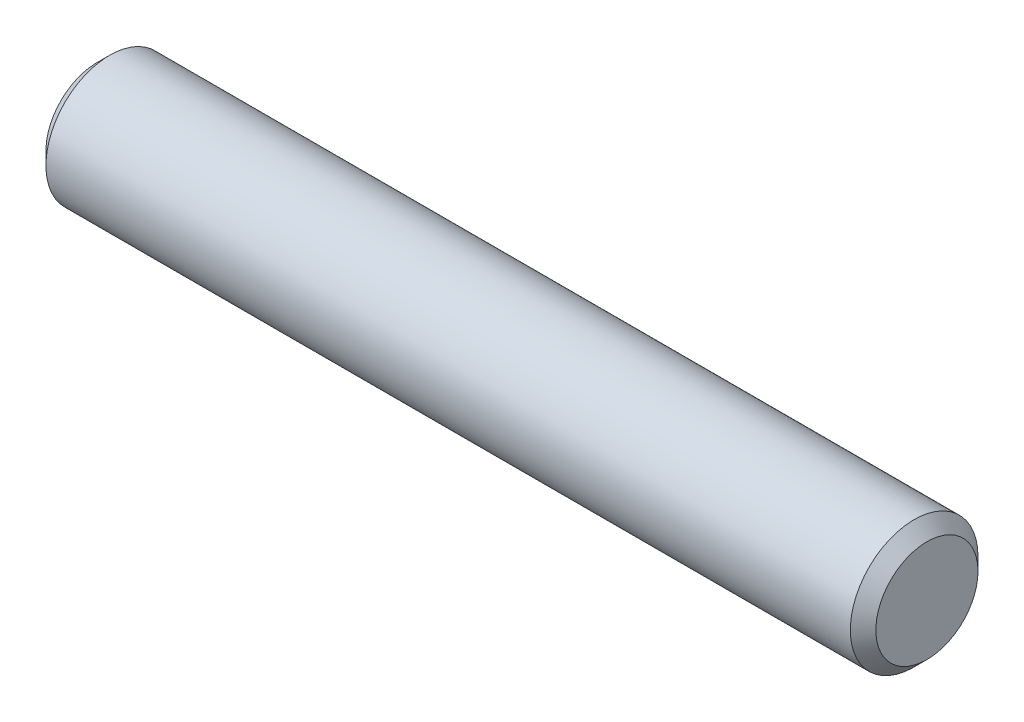
SolidWorks part; units mm, degrees
ref_plane "Front" through (0, 0, 0) normal (0, 0, 1) x (1, 0, 0)
ref_plane "Top" through (0, 0, 0) normal (0, 1, 0) x (1, 0, 0)
ref_plane "Right" through (0, 0, 0) normal (1, 0, 0) x (0, 0, -1)
sketch "Skizze1" plane through (0, 0, 0) normal (1, 0, 0) x (0, 0, -1)
  circle A0 centre (0, 0) radius 1.5
  dimension "D1" = 3
extrude "Aufsatz-Linear austragen1" add sketch "Skizze1" along normal mid plane 19.5
chamfer "Fase1" distance 0.3 angle 45 2 edges at (-9.75, 0, -1.5) (9.75, 0, -1.5)
